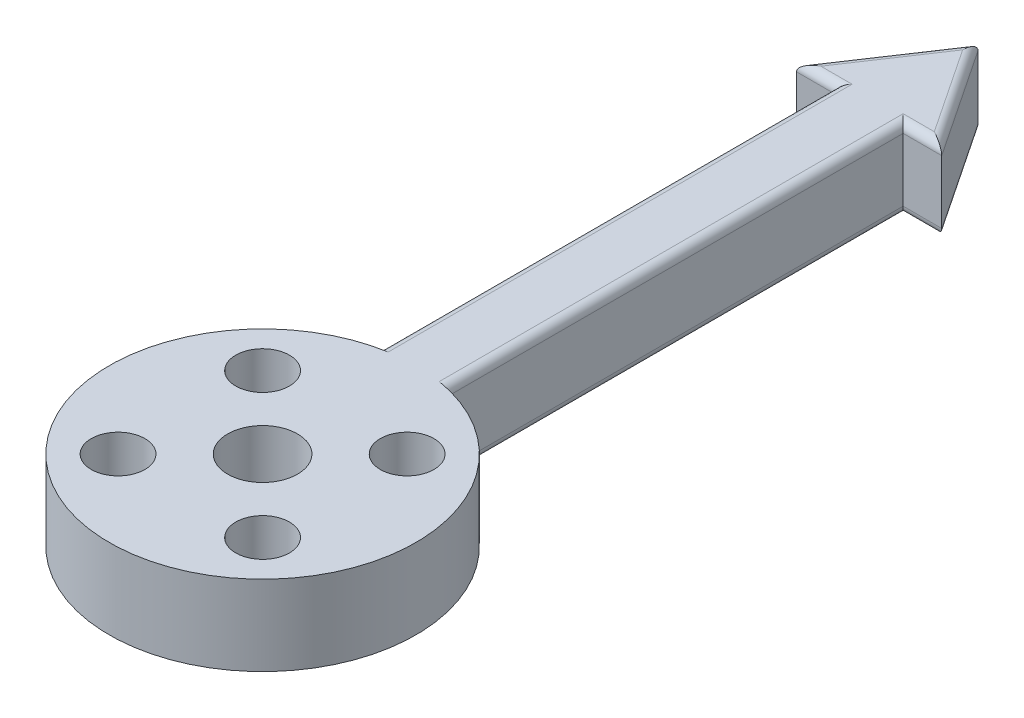
SolidWorks part; units mm, degrees
ref_plane "Front Plane" through (0, 0, 0) normal (0, 0, 1) x (1, 0, 0)
ref_plane "Top Plane" through (0, 0, 0) normal (0, 1, 0) x (1, 0, 0)
ref_plane "Right Plane" through (0, 0, 0) normal (1, 0, 0) x (0, 0, -1)
sketch "Sketch2" plane through (0, 0, 0) normal (0, 1, 0) x (1, 0, 0)
  line L6 (-4.2426, 4.2426) -> (4.2426, -4.2426) construction
  line L7 (-4.2426, -4.2426) -> (4.2426, 4.2426) construction
  circle A7 centre (0, 0) radius 2.05
  circle A20 centre (-4.2426, 4.2426) radius 1.575
  circle A21 centre (-4.2426, -4.2426) radius 1.575
  circle A22 centre (4.2426, -4.2426) radius 1.575
  circle A23 centre (4.2426, 4.2426) radius 1.575
  circle A36 centre (-4.2426, -4.2426) radius 2.95 construction
  circle A37 centre (-4.2426, 4.2426) radius 2.95 construction
  circle A38 centre (4.2426, -4.2426) radius 2.95 construction
  circle A39 centre (4.2426, 4.2426) radius 2.95 construction
  circle A42 centre (0, 0) radius 9
  point P44 (0, 0)
  point P45 (0, 0)
  point P55 (0, 0)
  dimension "D2" = 4.1
  dimension "D3" = 18
  dimension "D4" = 3.15
  dimension "D5" = 12
  dimension "D13" = 5.9
extrude "Boss-Extrude2" add sketch "Sketch2" along normal blind 4.7 separate body
sketch "Sketch3" plane through (0, 4.7, 0) normal (0, 1, 0) x (1, 0, 0)
  line L0 (0, 0) -> (0, 42) construction
  line L1 (-2, 35.6064) -> (-2, 8.775)
  line L2 (2, 35.6064) -> (2, 8.775)
  line L3 (-2, 22.1907) -> (2, 22.1907) construction
  line L4 (-2, 35.6064) -> (-4.265, 35.6064)
  line L5 (-4.265, 35.6064) -> (0, 42)
  line L6 (0, 42) -> (4.265, 35.6064)
  line L7 (4.265, 35.6064) -> (2, 35.6064)
  circle A0 centre (0, 0) radius 9 construction
  arc A1 (-2, 8.775) -> (2, 8.775) centre (0, 0) cw
  point P1 (-3.7802, 30.4157)
  point P9 (0, 22.1907)
  point P12 (-4.405, 35.8514)
  point P17 (-4.265, 35.6064)
  dimension "D1" = 42
  dimension "D2" = 4
extrude "Boss-Extrude3" add sketch "Sketch3" against normal up to surface (4.7 mm away) up to face at (0, 0, 9)
fillet "Fillet1" radius 0.5 12 edges at (2, 0, -22.1907) (2, 4.7, -22.1907) (2.1325, 0, -38.8032) (2.1325, 4.7, -38.8032) (3.1325, 0, -35.6064) (3.1325, 4.7, -35.6064) (-2.1325, 0, -38.8032) (-2.1325, 4.7, -38.8032) (-3.1325, 0, -35.6064) (-3.1325, 4.7, -35.6064) (-2, 0, -22.1907) (-2, 4.7, -22.1907)
